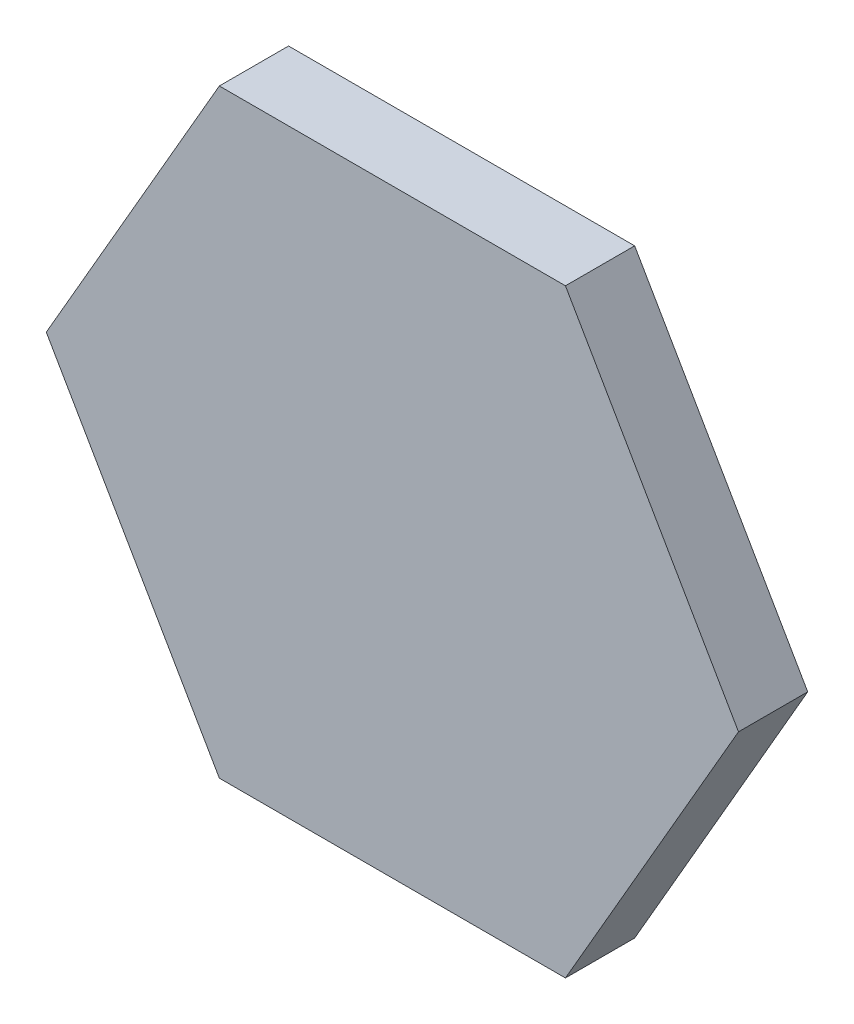
SolidWorks part; units mm, degrees
ref_plane "Front Plane" through (0, 0, 0) normal (0, 0, 1) x (1, 0, 0)
ref_plane "Top Plane" through (0, 0, 0) normal (0, 1, 0) x (1, 0, 0)
ref_plane "Right Plane" through (0, 0, 0) normal (1, 0, 0) x (0, 0, -1)
sketch "Sketch1" plane through (0, 0, 0) normal (0, 0, 1) x (1, 0, 0)
  line L1 (37.5, -64.9519) -> (75, 0)
  line L2 (75, 0) -> (37.5, 64.9519)
  line L3 (37.5, 64.9519) -> (-37.5, 64.9519)
  line L4 (-37.5, 64.9519) -> (-75, 0)
  line L5 (-75, 0) -> (-37.5, -64.9519)
  line L6 (-37.5, -64.9519) -> (37.5, -64.9519)
  circle A0 centre (0, 0) radius 64.9519 construction
  dimension "D1" = 150
extrude "Boss-Extrude1" add sketch "Sketch1" along normal blind 15
